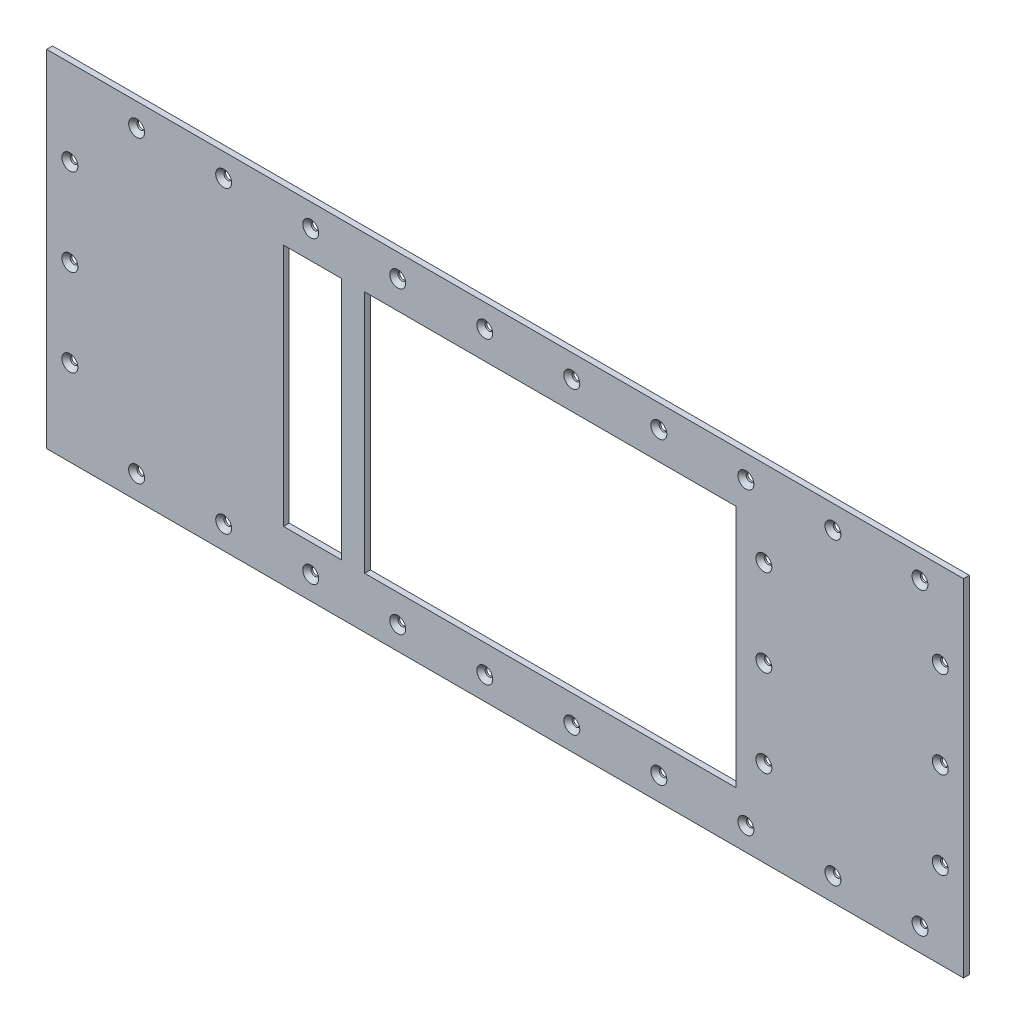
SolidWorks part; units mm, degrees
material "Простая углеродистая сталь"
ref_plane "Спереди" through (0, 0, 0) normal (0, 0, 1) x (1, 0, 0)
ref_plane "Сверху" through (0, 0, 0) normal (0, 1, 0) x (1, 0, 0)
ref_plane "Справа" through (0, 0, 0) normal (1, 0, 0) x (0, 0, -1)
sketch "Эскиз1" plane through (0, 0, 0) normal (0, 0, 1) x (1, 0, 0)
  line L0 (0, 149) -> (750, 149) construction
  line L1 (0, 0) -> (750, 0)
  line L3 (0, 298) -> (750, 298)
  line L4 (750, 0) -> (750, 298)
  line L5 (234, 44) -> (554, 44)
  line L6 (234, 44) -> (234, 254)
  line L7 (234, 254) -> (554, 254)
  line L8 (554, 44) -> (554, 254)
  line L10 (214, 254) -> (164, 254)
  line L11 (214, 254) -> (214, 44)
  line L12 (214, 44) -> (164, 44)
  line L13 (164, 254) -> (164, 44)
  line L14 (0, 0) -> (-40, 0)
  line L16 (0, 298) -> (-40, 298)
  line L17 (-40, 0) -> (-40, 298)
  dimension "D1" = 210
  dimension "D2" = 298
  dimension "D3" = 750
  dimension "D4" = 234
  dimension "D5" = 320
  dimension "D6" = 196
  dimension "D7" = 20
  dimension "D8" = 50
  dimension "D9" = 40
extrude "Бобышка-Вытянуть1" add sketch "Эскиз1" along normal blind 5
hole_wizard "Зенковка для винта с потайной головкой и внутренним шестигранником M61" positions "Эскиз3" profile "Эскиз2" countersink size "M6" standard "DIN" end condition through all
sketch "Эскиз3" plane through (0, 0, 5) normal (0, 0, 1) x (1, 0, 0)
  line L0 (750, 298) -> (-40, 298) construction
  line L1 (-40, 0) -> (750, 0) construction
  line L3 (750, 0) -> (750, 298) construction
  point P0 (37.5, 278)
  point P1 (37.5, 20)
  point P17 (112.5, 278)
  point P18 (112.5, 20)
  point P19 (187.5, 278)
  point P20 (187.5, 20)
  point P21 (262.5, 278)
  point P22 (262.5, 20)
  point P23 (337.5, 278)
  point P24 (337.5, 20)
  point P25 (412.5, 278)
  point P26 (412.5, 20)
  point P27 (487.5, 278)
  point P28 (487.5, 20)
  point P29 (562.5, 278)
  point P30 (562.5, 20)
  point P31 (637.5, 278)
  point P32 (637.5, 20)
  point P33 (712.5, 278)
  point P34 (712.5, 20)
  dimension "D1" = 20
  dimension "D2" = 20
  dimension "D5" = 75
  dimension "D6" = 37.5
  dimension "D4" = 10
sketch "Эскиз2" plane through (37.5, 278, 5) normal (1, 0, 0) x (0, -1, 0)
  line L0 (0, 0) -> (0, 5)
  line L1 (0, 5) -> (3.3, 5)
  line L2 (3.3, 5) -> (3.3, 3.555)
  line L3 (3.3, 3.555) -> (6.855, 0)
  line L5 (6.855, 0) -> (0, 0)
  line L6 (-3.3, 3.555) -> (-6.855, 0) construction
  line L11 (0, -6.35) -> (0, 107.95) construction
  dimension "Диаметр сквозного отверстия" = 6.6
  dimension "Глубина сквозного отверстия" = 5
  dimension "Диаметр передней зенковки" = 13.71
  dimension "Угол передней зенковки" = 90
hole_wizard "Зенковка для винта с потайной головкой и внутренним шестигранником M62" positions "Эскиз5" profile "Эскиз4" countersink size "M6" standard "DIN" end condition through all
sketch "Эскиз5" plane through (0, 0, 5) normal (0, 0, 1) x (1, 0, 0)
  line L1 (554, 44) -> (554, 254) construction
  line L2 (750, 0) -> (750, 298) construction
  line L3 (750, 298) -> (-40, 298) construction
  line L4 (730, 224) -> (730, 149) construction
  line L5 (-40, 298) -> (-40, 0) construction
  point P0 (-20, 224)
  point P1 (578, 224)
  point P3 (730, 224)
  point P25 (-20, 149)
  point P26 (578, 149)
  point P27 (730, 149)
  point P28 (-20, 74)
  point P29 (578, 74)
  point P30 (730, 74)
  dimension "D1" = 20
  dimension "D2" = 24
  dimension "D3" = 20
  dimension "D4" = 74
  dimension "D6" = 75
  dimension "D5" = 3
sketch "Эскиз4" plane through (-20, 224, 5) normal (1, 0, 0) x (0, -1, 0)
  line L0 (0, 0) -> (0, 5)
  line L1 (0, 5) -> (3.3, 5)
  line L2 (3.3, 5) -> (3.3, 3.555)
  line L3 (3.3, 3.555) -> (6.855, 0)
  line L5 (6.855, 0) -> (0, 0)
  line L6 (-3.3, 3.555) -> (-6.855, 0) construction
  line L11 (0, -6.35) -> (0, 107.95) construction
  dimension "Диаметр сквозного отверстия" = 6.6
  dimension "Глубина сквозного отверстия" = 5
  dimension "Диаметр передней зенковки" = 13.71
  dimension "Угол передней зенковки" = 90
